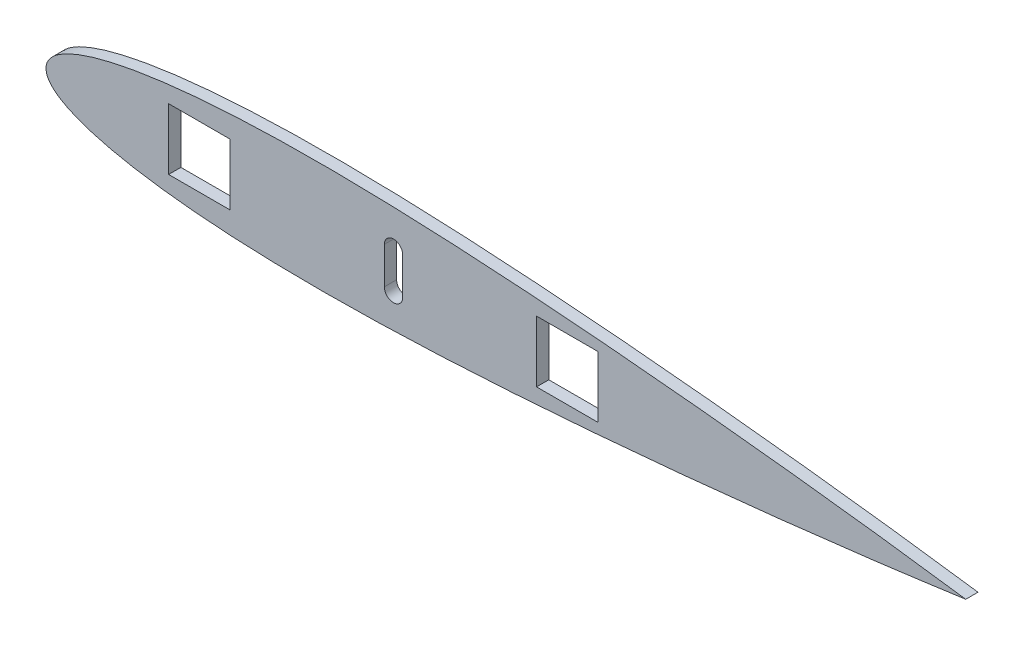
SolidWorks part; units mm, degrees
ref_plane "Front Plane" through (0, 0, 0) normal (0, 0, 1) x (1, 0, 0)
ref_plane "Top Plane" through (0, 0, 0) normal (0, 1, 0) x (1, 0, 0)
ref_plane "Right Plane" through (0, 0, 0) normal (1, 0, 0) x (0, 0, -1)
curve "Curve1"
  spline degree 3 poles (0, 0, 0) (0.0001, 0.0014, 0) (0.0004, 0.0044, 0) (0.0023, 0.0087, 0) (0.0053, 0.0128, 0) (0.0094, 0.0167, 0) (0.0147, 0.0206, 0) (0.0211, 0.0243, 0) (0.0286, 0.0279, 0) (0.0372, 0.0313, 0) (0.0468, 0.0347, 0) (0.0576, 0.0378, 0) (0.0693, 0.0408, 0) (0.0821, 0.0436, 0) (0.0958, 0.0462, 0) (0.1104, 0.0486, 0) (0.126, 0.0507, 0) (0.1425, 0.0527, 0) (0.1597, 0.0544, 0) (0.1778, 0.056, 0) (0.1966, 0.0572, 0) (0.2162, 0.0583, 0) (0.2364, 0.0591, 0) (0.2572, 0.0596, 0) (0.2786, 0.06, 0) (0.3005, 0.0601, 0) (0.3228, 0.0599, 0) (0.3456, 0.0596, 0) (0.3688, 0.0591, 0) (0.3922, 0.0583, 0) (0.4159, 0.0574, 0) (0.4398, 0.0563, 0) (0.4638, 0.0551, 0) (0.4879, 0.0537, 0) (0.5121, 0.0522, 0) (0.5362, 0.0505, 0) (0.5602, 0.0488, 0) (0.5841, 0.0469, 0) (0.6078, 0.045, 0) (0.6313, 0.043, 0) (0.6544, 0.0409, 0) (0.6772, 0.0388, 0) (0.6995, 0.0367, 0) (0.7214, 0.0345, 0) (0.7428, 0.0324, 0) (0.7636, 0.0302, 0) (0.7838, 0.028, 0) (0.8033, 0.0259, 0) (0.8222, 0.0238, 0) (0.8402, 0.0217, 0) (0.8575, 0.0196, 0) (0.874, 0.0177, 0) (0.8895, 0.0158, 0) (0.9042, 0.014, 0) (0.9179, 0.0122, 0) (0.9307, 0.0106, 0) (0.9424, 0.0091, 0) (0.9531, 0.0077, 0) (0.9627, 0.0064, 0) (0.9713, 0.0052, 0) (0.9788, 0.0042, 0) (0.9851, 0.0033, 0) (0.9903, 0.0026, 0) (0.9944, 0.002, 0) (0.9973, 0.0016, 0) (0.999, 0.0014, 0) (0.9998, 0.0013, 0) (1, 0.0013, 0) knots 0 0 0 0 0.004218 0.008652 0.013562 0.019137 0.0255 0.032726 0.040862 0.04993 0.05994 0.070892 0.082777 0.095581 0.109286 0.123868 0.139301 0.155557 0.172602 0.190404 0.208924 0.228125 0.247965 0.268401 0.289388 0.310881 0.332832 0.35519 0.377906 0.400928 0.424203 0.447679 0.471299 0.49501 0.518757 0.542484 0.566136 0.589657 0.612992 0.636087 0.658886 0.681338 0.703388 0.724985 0.746079 0.766619 0.786556 0.805845 0.82444 0.842296 0.859372 0.875627 0.891023 0.905523 0.919093 0.9317 0.943314 0.953909 0.963457 0.971937 0.979328 0.985613 0.990775 0.994804 0.997688 0.999422 1 1 1 1
sketch "Sketch1" plane through (0, 0, 0) normal (0, 0, 1) x (1, 0, 0)
  line L0 (0, 0) -> (1, 0.0013) construction
  line L1 (0, 0) -> (150, 0) construction
  spline S0 degree 3 poles (0, 0) (0.0001, -0.0014) (0.0004, -0.0044) (0.0023, -0.0087) (0.0053, -0.0128) (0.0095, -0.0167) (0.0148, -0.0206) (0.0212, -0.0243) (0.0287, -0.0278) (0.0373, -0.0313) (0.0469, -0.0345) (0.0577, -0.0377) (0.0739, -0.0417) (0.0967, -0.0462) (0.127, -0.0507) (0.1606, -0.0543) (0.1975, -0.0569) (0.2444, -0.0589) (0.3019, -0.0596) (0.3697, -0.0584) (0.4484, -0.0551) (0.536, -0.0495) (0.6299, -0.0417) (0.7253, -0.0325) (0.8209, -0.022) (0.9105, -0.011) (0.9695, -0.0031) (0.9967, 0.0008) (0.9998, 0.0012) (1, 0.0013) knots 0 0 0 0 0.004218 0.008652 0.013562 0.019137 0.0255 0.032726 0.040862 0.04993 0.05994 0.070892 0.082777 0.109286 0.139301 0.172602 0.208924 0.247965 0.310881 0.377906 0.447679 0.542484 0.636087 0.724985 0.82444 0.919093 0.990775 0.999422 1 1 1 1 construction
  spline S1 degree 3 poles (-2926.8265, 657.545) (12.565, -3.5048) (-0.1383, -0.3039) (0.0023, 0.0087) (0.0053, 0.0128) (0.0094, 0.0167) (0.0147, 0.0206) (0.0211, 0.0243) (0.0286, 0.0279) (0.0372, 0.0313) (0.0468, 0.0347) (0.0576, 0.0378) (0.0738, 0.0419) (0.0966, 0.0465) (0.1268, 0.051) (0.1605, 0.0547) (0.1973, 0.0574) (0.2443, 0.0595) (0.3017, 0.0603) (0.3696, 0.0593) (0.4482, 0.0562) (0.5358, 0.0508) (0.6298, 0.0433) (0.7252, 0.0344) (0.8208, 0.0241) (0.9105, 0.0133) (0.9689, 0.0056) (0.9959, 0.0018) (2.1649, -0.1618) (3.2618, -0.8218) (420.994, 2970.3371) knots -0.978191 -0.978191 -0.978191 -0.978191 0.004218 0.008652 0.013562 0.019137 0.0255 0.032726 0.040862 0.04993 0.05994 0.070892 0.082777 0.109286 0.139301 0.172602 0.208924 0.247965 0.310881 0.377906 0.447679 0.542484 0.636087 0.724985 0.82444 0.919093 0.990775 0.997688 0.999422 4.46377 4.46377 4.46377 4.46377 only from (0, 0) to (1, 0.0013) construction
  spline S2 degree 3 poles (0, 0) (0.0001, 0.0014) (0.0004, 0.0044) (0.0023, 0.0087) (0.0053, 0.0128) (0.0094, 0.0167) (0.0147, 0.0206) (0.0211, 0.0243) (0.0286, 0.0279) (0.0372, 0.0313) (0.0468, 0.0347) (0.0576, 0.0378) (0.0738, 0.0419) (0.0966, 0.0465) (0.1268, 0.051) (0.1605, 0.0547) (0.1973, 0.0574) (0.2443, 0.0595) (0.3017, 0.0603) (0.3696, 0.0593) (0.4482, 0.0562) (0.5358, 0.0508) (0.6298, 0.0433) (0.7252, 0.0344) (0.8208, 0.0241) (0.9105, 0.0133) (0.9695, 0.0055) (0.9967, 0.0017) (0.9998, 0.0013) (1, 0.0013) knots 0 0 0 0 0.004218 0.008652 0.013562 0.019137 0.0255 0.032726 0.040862 0.04993 0.05994 0.070892 0.082777 0.109286 0.139301 0.172602 0.208924 0.247965 0.310881 0.377906 0.447679 0.542484 0.636087 0.724985 0.82444 0.919093 0.990775 0.999422 1 1 1 1 construction
  spline S3 degree 3 poles (0, 0) (0.0177, 0.2156) (0.0541, 0.658) (0.3432, 1.2989) (0.7935, 1.9155) (1.4186, 2.5104) (2.2104, 3.0858) (3.1698, 3.6423) (4.2948, 4.1791) (5.5834, 4.6951) (7.0332, 5.1888) (8.641, 5.6584) (11.0809, 6.2729) (14.5024, 6.9555) (19.0333, 7.6278) (24.0847, 8.1695) (29.6103, 8.5734) (36.6534, 8.8842) (45.2686, 8.9945) (55.4492, 8.824) (67.2472, 8.3466) (80.3841, 7.5249) (94.4751, 6.3814) (108.7842, 5.0156) (123.1279, 3.4613) (136.5791, 1.8282) (145.4208, 0.6448) (149.5052, 0.0701) (149.9708, 0.0041) (150, 0) knots 0 0 0 0 0.004218 0.008652 0.013562 0.019137 0.0255 0.032726 0.040862 0.04993 0.05994 0.070892 0.082777 0.109286 0.139301 0.172602 0.208924 0.247965 0.310881 0.377906 0.447679 0.542484 0.636087 0.724985 0.82444 0.919093 0.990775 0.999422 1 1 1 1
  spline S4 degree 3 poles (0, 0) (0.0177, -0.2156) (0.0541, -0.658) (0.3432, -1.2989) (0.7935, -1.9155) (1.4186, -2.5104) (2.2104, -3.0858) (3.1698, -3.6423) (4.2948, -4.1791) (5.5834, -4.6951) (7.0332, -5.1888) (8.641, -5.6584) (11.0809, -6.2729) (14.5024, -6.9555) (19.0333, -7.6278) (24.0847, -8.1695) (29.6103, -8.5734) (36.6534, -8.8842) (45.2686, -8.9945) (55.4492, -8.824) (67.2472, -8.3466) (80.3841, -7.5249) (94.4751, -6.3814) (108.7842, -5.0156) (123.1279, -3.4613) (136.5791, -1.8282) (145.4208, -0.6448) (149.5052, -0.0701) (149.9708, -0.0041) (150, 0) knots 0 0 0 0 0.004218 0.008652 0.013562 0.019137 0.0255 0.032726 0.040862 0.04993 0.05994 0.070892 0.082777 0.109286 0.139301 0.172602 0.208924 0.247965 0.310881 0.377906 0.447679 0.542484 0.636087 0.724985 0.82444 0.919093 0.990775 0.999422 1 1 1 1
  dimension "D1" = 150
extrude "Boss-Extrude1" add sketch "Sketch1" along normal blind 2
sketch "Sketch2" plane through (0, 0, 2) normal (0, 0, 1) x (1, 0, 0)
  line L0 (0, 0) -> (150, 0) construction
  line L1 (20, 5) -> (30, 5)
  line L2 (20, 5) -> (20, -5)
  line L3 (20, -5) -> (30, -5)
  line L4 (30, 5) -> (30, -5)
  line L5 (80, 5) -> (90, 5)
  line L6 (80, 5) -> (80, -5)
  line L7 (80, -5) -> (90, -5)
  line L8 (90, 5) -> (90, -5)
  spline S2 degree 3 poles (-3906.8979, -852.5952) (79.5557, 38.8979) (-4.2663, 8.9199) (0.3432, -1.2989) (0.7935, -1.9155) (1.4186, -2.5104) (2.2104, -3.0858) (3.1698, -3.6423) (4.2948, -4.1791) (5.5834, -4.6951) (7.0332, -5.1888) (8.641, -5.6584) (11.0809, -6.2729) (14.5024, -6.9555) (19.0333, -7.6278) (24.0847, -8.1695) (29.6103, -8.5734) (36.6534, -8.8842) (45.2686, -8.9945) (55.4492, -8.824) (67.2472, -8.3466) (80.3841, -7.5249) (94.4751, -6.3814) (108.7842, -5.0156) (123.1279, -3.4613) (136.5791, -1.8282) (145.4208, -0.6448) (189.581, 5.5694) (229.7046, 14.2243) (830.7442, -3940.0027) knots -0.202685 -0.202685 -0.202685 -0.202685 0.004218 0.008652 0.013562 0.019137 0.0255 0.032726 0.040862 0.04993 0.05994 0.070892 0.082777 0.109286 0.139301 0.172602 0.208924 0.247965 0.310881 0.377906 0.447679 0.542484 0.636087 0.724985 0.82444 0.919093 0.990775 0.999422 1.793868 1.793868 1.793868 1.793868 only from (0, 0) to (150, 0)
  spline S3 degree 3 poles (830.7517, 3940.0522) (229.7049, -14.2244) (189.5812, -5.5695) (145.4208, 0.6448) (136.5791, 1.8282) (123.1279, 3.4613) (108.7842, 5.0156) (94.4751, 6.3814) (80.3841, 7.5249) (67.2472, 8.3466) (55.4492, 8.824) (45.2686, 8.9945) (36.6534, 8.8842) (29.6103, 8.5734) (24.0847, 8.1695) (19.0333, 7.6278) (14.5024, 6.9555) (11.0809, 6.2729) (8.641, 5.6584) (7.0332, 5.1888) (5.5834, 4.6951) (4.2948, 4.1791) (3.1698, 3.6423) (2.2104, 3.0858) (1.4186, 2.5104) (0.7935, 1.9155) (0.3432, 1.2989) (-4.2664, -8.9202) (79.5612, -38.8998) (-3907.2989, 852.6849) knots -0.793872 -0.793872 -0.793872 -0.793872 0.000578 0.009225 0.080907 0.17556 0.275015 0.363913 0.457516 0.552321 0.622094 0.689119 0.752035 0.791076 0.827398 0.860699 0.890714 0.917223 0.929108 0.94006 0.95007 0.959138 0.967274 0.9745 0.980863 0.986438 0.991348 0.995782 1.202692 1.202692 1.202692 1.202692 only from (150, 0) to (0, 0)
  spline S4 degree 3 poles (0, 0) (0.0177, -0.2156) (0.0541, -0.658) (0.3432, -1.2989) (0.7935, -1.9155) (1.4186, -2.5104) (2.2104, -3.0858) (3.1698, -3.6423) (4.2948, -4.1791) (5.5834, -4.6951) (7.0332, -5.1888) (8.641, -5.6584) (11.0809, -6.2729) (14.5024, -6.9555) (19.0333, -7.6278) (24.0847, -8.1695) (29.6103, -8.5734) (36.6534, -8.8842) (45.2686, -8.9945) (55.4492, -8.824) (67.2472, -8.3466) (80.3841, -7.5249) (94.4751, -6.3814) (108.7842, -5.0156) (123.1279, -3.4613) (136.5791, -1.8282) (145.4208, -0.6448) (149.5052, -0.0701) (149.9708, -0.0041) (150, 0) knots 0 0 0 0 0.004218 0.008652 0.013562 0.019137 0.0255 0.032726 0.040862 0.04993 0.05994 0.070892 0.082777 0.109286 0.139301 0.172602 0.208924 0.247965 0.310881 0.377906 0.447679 0.542484 0.636087 0.724985 0.82444 0.919093 0.990775 0.999422 1 1 1 1
  spline S5 degree 3 poles (150, 0) (149.9708, 0.0041) (149.5052, 0.0701) (145.4208, 0.6448) (136.5791, 1.8282) (123.1279, 3.4613) (108.7842, 5.0156) (94.4751, 6.3814) (80.3841, 7.5249) (67.2472, 8.3466) (55.4492, 8.824) (45.2686, 8.9945) (36.6534, 8.8842) (29.6103, 8.5734) (24.0847, 8.1695) (19.0333, 7.6278) (14.5024, 6.9555) (11.0809, 6.2729) (8.641, 5.6584) (7.0332, 5.1888) (5.5834, 4.6951) (4.2948, 4.1791) (3.1698, 3.6423) (2.2104, 3.0858) (1.4186, 2.5104) (0.7935, 1.9155) (0.3432, 1.2989) (0.0541, 0.658) (0.0177, 0.2156) (0, 0) knots 0 0 0 0 0.000578 0.009225 0.080907 0.17556 0.275015 0.363913 0.457516 0.552321 0.622094 0.689119 0.752035 0.791076 0.827398 0.860699 0.890714 0.917223 0.929108 0.94006 0.95007 0.959138 0.967274 0.9745 0.980863 0.986438 0.991348 0.995782 1 1 1 1
  dimension "D2" = 10
  dimension "D3" = 10
  dimension "D4" = 5
  dimension "D5" = 5
  dimension "D6" = 20
  dimension "D7" = 50
  dimension "D1" = 0
extrude "Cut-Extrude1" cut sketch "Sketch2" against normal blind 2 contours L6 L7 L8 L5 | L2 L3 L4 L1
sketch "Sketch3" plane through (0, 0, 2) normal (0, 0, 1) x (1, 0, 0)
  line L0 (56.678, -3.2792) -> (56.678, 2.7212) construction
  line L1 (55.1779, -3.2792) -> (55.1779, 2.7212)
  line L2 (58.1781, -3.2792) -> (58.1781, 2.7212)
  arc A0 (55.1779, -3.2792) -> (58.1781, -3.2792) centre (56.678, -3.2792) ccw
  arc A1 (58.1781, 2.7212) -> (55.1779, 2.7212) centre (56.678, 2.7212) ccw
  point P2 (56.678, -0.279)
extrude "Cut-Extrude2" cut sketch "Sketch3" against normal blind 2
